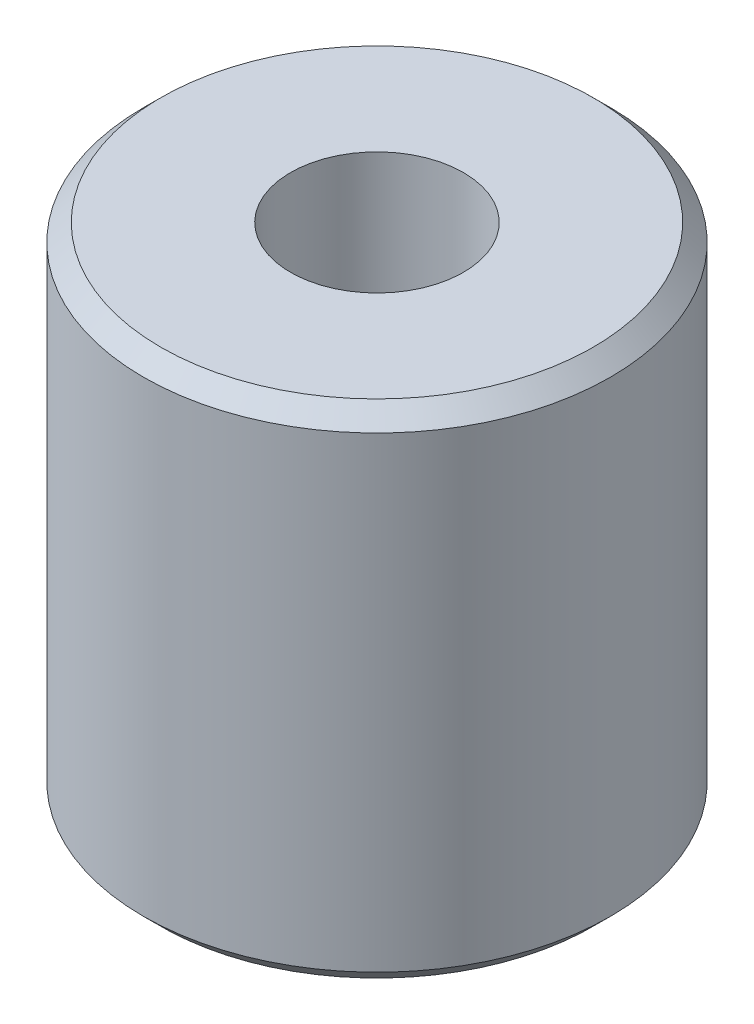
SolidWorks part; units mm, degrees
ref_plane "Plan1" through (0, 0, 0) normal (0, 0, 1) x (1, 0, 0)
ref_plane "Plan2" through (0, 0, 0) normal (0, 1, 0) x (1, 0, 0)
ref_plane "Plan3" through (0, 0, 0) normal (1, 0, 0) x (0, 0, -1)
sketch "Esquisse1" plane through (0, 0, 0) normal (0, 0, 1) x (1, 0, 0)
  line L0 (0, 0) -> (0, 100) construction
  line L1 (0, 0) -> (13.5, 0)
  line L2 (13.5, 0) -> (13.5, 29)
  line L3 (13.5, 29) -> (0, 29)
  line L4 (0, 29) -> (0, 0)
  dimension "D1" = 29
  dimension "D2" = 13.5
revolve "Base-Révolution" add sketch "Esquisse1" angle 360 about L0
sketch "Esquisse2" plane through (0, 0, 0) normal (0, -1, 0) x (1, 0, 0)
  circle A0 centre (0, 0) radius 11.5
extrude "Enlèv. mat.-Extru.1" cut sketch "Esquisse2" against normal blind 4
chamfer "Chanfrein1" distance 1 angle 45
sketch "Esquisse3" plane through (0, 0, 0) normal (0, 1, 0) x (1, 0, 0)
  line L0 (0, 0) -> (0, 20) construction
  line L1 (0, 12.2) -> (16.5, 12.2)
  line L2 (16.5, 12.2) -> (21.5, 17.2)
  line L3 (21.5, 17.2) -> (0, 17.2)
  line L4 (0, 17.2) -> (0, 12.2)
  dimension "D1" = 12.2
  dimension "D2" = 135
  dimension "D3" = 16.5
  dimension "D4" = 5
revolve "Enlèvement de matière-Révolution1" cut sketch "Esquisse3" angle 360 about L0
sketch "Esquisse4" plane through (0, 4, 0) normal (0, -1, 0) x (1, 0, 0)
  circle A0 centre (0, 0) radius 8
extrude "Enlèv. mat.-Extru.2" cut sketch "Esquisse4" against normal blind 10
sketch "Esquisse5" plane through (0, 14, 0) normal (0, -1, 0) x (1, 0, 0)
  circle A0 centre (0, 0) radius 5
extrude "Enlèv. mat.-Extru.3" cut sketch "Esquisse5" against normal through all
sketch "Esquisse6" plane through (0, 0, -12.2) normal (0, 0, -1) x (-1, 0, 0)
  line L0 (0, 4) -> (0, 0) construction
  line L1 (-2.7221, 0) -> (2.7221, 0) construction
  circle A0 centre (0, 8) radius 3
  dimension "D1" = 6
  dimension "D2" = 8
extrude "Enlèv. mat.-Extru.4" cut sketch "Esquisse6" against normal up to next
